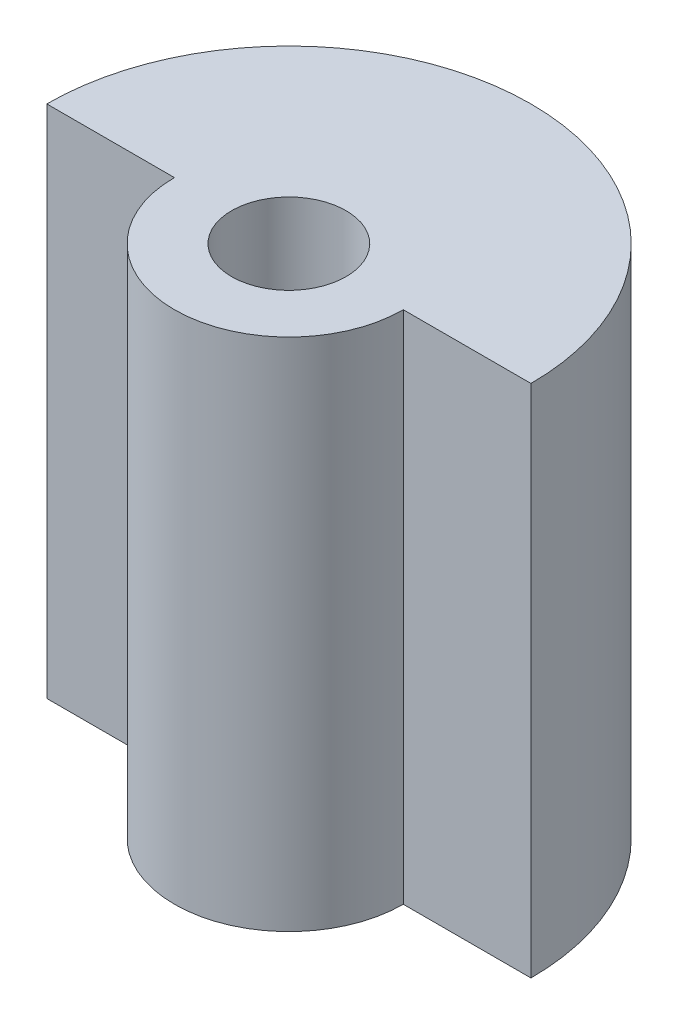
SolidWorks part; units mm, degrees
ref_plane "Front Plane" through (0, 0, 0) normal (0, 0, 1) x (1, 0, 0)
ref_plane "Top Plane" through (0, 0, 0) normal (0, 1, 0) x (1, 0, 0)
ref_plane "Right Plane" through (0, 0, 0) normal (1, 0, 0) x (0, 0, -1)
sketch "Sketch1" plane through (0, 0, 0) normal (0, 1, 0) x (1, 0, 0)
  line L0 (-2.1157, 0) -> (-1, 0)
  line L1 (1, 0) -> (2.1157, 0)
  arc A1 (-1, 0) -> (1, 0) centre (0, 0) ccw
  arc A2 (2.1157, 0) -> (-2.1157, 0) centre (0, 0) ccw
  point P4 (0, 0)
  dimension "D2" = 2
extrude "Boss-Extrude1" add sketch "Sketch1" along normal blind 4.5
sketch "Sketch2" plane through (0, 4.5, 0) normal (0, 1, 0) x (1, 0, 0)
  circle A0 centre (0, 0) radius 0.5
  dimension "D1" = 1
extrude "Cut-Extrude1" cut sketch "Sketch2" against normal blind 4.5
